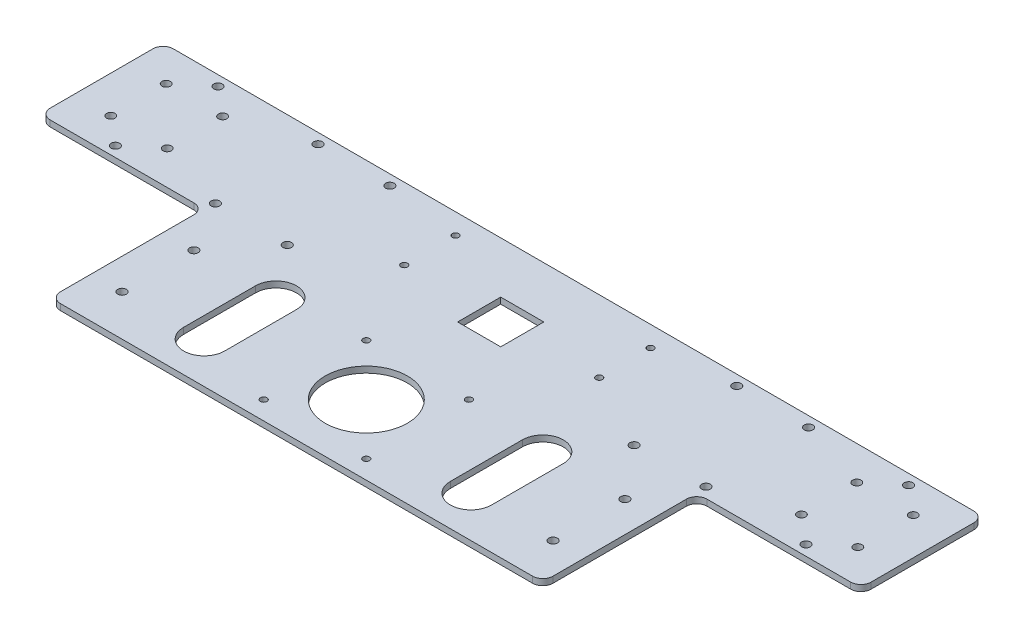
SolidWorks part; units mm, degrees
material "Thornel Mat VMA"
ref_plane "前视基准面" through (0, 0, 0) normal (0, 0, 1) x (1, 0, 0)
ref_plane "上视基准面" through (0, 0, 0) normal (0, 1, 0) x (1, 0, 0)
ref_plane "右视基准面" through (0, 0, 0) normal (1, 0, 0) x (0, 0, -1)
sketch "草图1" plane through (0, 0, 0) normal (0, 1, 0) x (1, 0, 0)
  line L0 (32.8259, -88.8718) -> (32.8259, 46.1282) construction
  line L1 (-167.1741, -13.8718) -> (232.8259, -13.8718)
  line L2 (-167.1741, -13.8718) -> (-167.1741, 46.1282)
  line L3 (-167.1741, 46.1282) -> (232.8259, 46.1282)
  line L4 (232.8259, -13.8718) -> (232.8259, 46.1282)
  line L5 (-14.6741, 36.1282) -> (80.3259, 36.1282) construction
  line L6 (-14.6741, 11.1282) -> (80.3259, 11.1282) construction
  line L7 (-87.1741, -88.8718) -> (152.8259, -88.8718)
  line L8 (-87.1741, -88.8718) -> (-87.1741, -13.8718)
  line L9 (-87.1741, -13.8718) -> (152.8259, -13.8718)
  line L10 (152.8259, -88.8718) -> (152.8259, -13.8718)
  line L11 (22.3259, 10.6282) -> (43.3259, 10.6282) construction
  line L12 (22.3259, 0.1282) -> (43.3259, 0.1282)
  line L13 (22.3259, 0.1282) -> (22.3259, 21.1282)
  line L14 (22.3259, 21.1282) -> (43.3259, 21.1282)
  line L15 (43.3259, 0.1282) -> (43.3259, 21.1282)
  line L16 (7.8259, -54.8718) -> (57.8259, -54.8718) construction
  line L17 (7.8259, -29.8718) -> (57.8259, -29.8718) construction
  line L18 (7.8259, -29.8718) -> (7.8259, -79.8718) construction
  line L19 (7.8259, -79.8718) -> (57.8259, -79.8718) construction
  line L20 (57.8259, -29.8718) -> (57.8259, -79.8718) construction
  line L21 (32.8259, 21.1282) -> (32.8259, 0.1282) construction
  line L22 (7.8259, -29.8718) -> (29.2904, -51.3362) construction
  line L23 (57.8259, -29.8718) -> (7.8259, -79.8718) construction
  line L31 (36.3615, -58.4073) -> (57.8259, -79.8718) construction
  circle A0 centre (-14.6741, 36.1282) radius 1.6
  circle A1 centre (-14.6741, 11.1282) radius 1.6
  circle A2 centre (80.3259, 11.1282) radius 1.6
  circle A3 centre (80.3259, 36.1282) radius 1.6
  circle A4 centre (7.8259, -29.8718) radius 1.6
  circle A5 centre (7.8259, -79.8718) radius 1.6
  circle A6 centre (57.8259, -79.8718) radius 1.6
  circle A7 centre (57.8259, -29.8718) radius 1.6
  circle A8 centre (32.8259, -54.8718) radius 20
  point P0 (0, 0)
  point P6 (0, -121.2547)
  point P16 (32.8259, 36.1282)
  point P19 (32.8259, 11.1282)
  point P23 (32.8259, 13.1501)
  point P30 (32.8259, -20.0664)
  point P35 (32.8259, -29.8718)
  point P44 (4.2904, -33.4073)
  point P45 (54.2904, -83.4073)
  point P46 (11.3615, -26.3362)
  point P47 (61.3615, -76.3362)
  point P48 (54.2904, -26.3362)
  point P49 (4.2904, -76.3362)
  point P50 (61.3615, -33.4073)
  point P51 (11.3615, -83.4073)
  dimension "D8" = 21
  dimension "D13" = 3.2
  dimension "D9" = 40
  dimension "D1" = 400
  dimension "D2" = 60
  dimension "D3" = 75
  dimension "D4" = 240
  dimension "D5" = 10
  dimension "D6" = 95
  dimension "D7" = 25
  dimension "D10" = 30
  dimension "D11" = 15
  dimension "D12" = 50
  dimension "D14" = 10.5
extrude "构型与裁判孔" add sketch "草图1" along normal blind 3 contours L1 L4 L3 L2 A3 L15 L12 L13 L14 A0 A1 A2 A4 A7 | L7 L10 L1 L8 A6 A5
sketch "草图2" plane through (0, 3, 0) normal (0, 1, 0) x (1, 0, 0)
  line L0 (-167.1741, 16.1282) -> (232.8259, 16.1282) construction
  line L1 (-167.1741, -13.8718) -> (-167.1741, 46.1282) construction
  line L2 (232.8259, -13.8718) -> (232.8259, 46.1282) construction
  line L3 (32.8259, 46.1282) -> (32.8259, -88.8718) construction
  line L4 (-167.1741, 46.1282) -> (232.8259, 46.1282) construction
  line L5 (-87.1741, -88.8718) -> (152.8259, -88.8718) construction
  line L6 (-149.1741, 2.6282) -> (-149.1741, 29.6282) construction
  line L7 (-121.6741, 2.6282) -> (-121.6741, 29.6282) construction
  line L8 (-149.1741, 29.6282) -> (-121.6741, 29.6282) construction
  line L9 (-51.6741, -8.8718) -> (-51.6741, 41.1282) construction
  line L10 (-135.4241, 29.6282) -> (-135.4241, 46.1282) construction
  line L11 (-135.4241, 41.1282) -> (-86.6741, 41.1282) construction
  circle A0 centre (-149.1741, 29.6282) radius 2.05
  circle A1 centre (-149.1741, 2.6282) radius 2.05
  circle A2 centre (-121.6741, 29.6282) radius 2.05
  circle A3 centre (-121.6741, 2.6282) radius 2.05
  circle A4 centre (-51.6741, 41.1282) radius 2.1
  circle A5 centre (-86.6741, 41.1282) radius 2.1
  circle A6 centre (-51.6741, -8.8718) radius 2.1
  circle A7 centre (-86.6741, -8.8718) radius 2.1
  circle A8 centre (-135.4241, 41.1282) radius 2.1
  circle A9 centre (-135.4241, -8.8718) radius 2.1
  circle A10 centre (201.0759, -8.8718) radius 2.1
  circle A11 centre (201.0759, 41.1282) radius 2.1
  circle A12 centre (152.3259, -8.8718) radius 2.1
  circle A13 centre (117.3259, -8.8718) radius 2.1
  circle A14 centre (152.3259, 41.1282) radius 2.1
  circle A15 centre (117.3259, 41.1282) radius 2.1
  circle A16 centre (187.3259, 2.6282) radius 2.05
  circle A17 centre (187.3259, 29.6282) radius 2.05
  circle A18 centre (214.8259, 2.6282) radius 2.05
  circle A19 centre (214.8259, 29.6282) radius 2.05
  point P15 (-149.1741, 16.1282)
  point P20 (-121.6741, 16.1282)
  point P25 (-51.6741, 16.1282)
  dimension "D2" = 4.1
  dimension "D4" = 5
  dimension "D5" = 4.2
  dimension "D7" = 2
  dimension "D8" = 18
  dimension "D3" = 45.5
  dimension "D1" = 27
  dimension "D6" = 70
extrude "切除-拉伸1" cut sketch "草图2" against normal through all
fillet "圆角1" radius 5 8 edges at (-87.1741, 1.5, 13.8718) (152.8259, 1.5, 13.8718) (-167.1741, 1.5, 13.8718) (-167.1741, 1.5, -46.1282) (232.8259, 1.5, -46.1282) (232.8259, 1.5, 13.8718) (152.8259, 1.5, 88.8718) (-87.1741, 1.5, 88.8718)
sketch "Sketch1" plane through (0, 0, 0) normal (0, 1, 0) x (1, 0, 0)
  line L0 (-162.1741, -13.8718) -> (-92.1741, -13.8718) construction
  line L1 (-87.1741, -83.8718) -> (-87.1741, -18.8718) construction
  line L2 (32.8259, 46.1282) -> (32.8259, -164.9495) construction
  line L3 (-162.1741, 46.1282) -> (227.8259, 46.1282) construction
  line L4 (-72.1741, -33.8718) -> (-72.1741, -68.8718) construction
  line L5 (-32.1741, -33.8718) -> (-32.1741, -68.8718) construction
  line L6 (-32.1741, -68.8718) -> (-32.1741, -33.8718) construction
  line L7 (-42.1741, -68.8718) -> (-42.1741, -33.8718)
  line L8 (-22.1741, -68.8718) -> (-22.1741, -33.8718)
  line L9 (97.8259, -68.8718) -> (97.8259, -33.8718) construction
  line L10 (107.8259, -68.8718) -> (107.8259, -33.8718)
  line L11 (87.8259, -68.8718) -> (87.8259, -33.8718)
  circle A0 centre (-72.1741, -33.8718) radius 2.1
  circle A1 centre (-72.1741, -68.8718) radius 2.1
  circle A2 centre (137.8259, -68.8718) radius 2.1
  circle A3 centre (137.8259, -33.8718) radius 2.1
  arc A4 (-42.1741, -68.8718) -> (-22.1741, -68.8718) centre (-32.1741, -68.8718) ccw
  arc A5 (-22.1741, -33.8718) -> (-42.1741, -33.8718) centre (-32.1741, -33.8718) ccw
  arc A6 (107.8259, -68.8718) -> (87.8259, -68.8718) centre (97.8259, -68.8718) cw
  arc A7 (87.8259, -33.8718) -> (107.8259, -33.8718) centre (97.8259, -33.8718) cw
  point P18 (-32.1741, -51.3718)
  point P20 (-32.1741, -51.3718)
  point P27 (97.8259, -51.3718)
  dimension "D1" = 4.2
  dimension "D2" = 20
  dimension "D3" = 35
  dimension "D4" = 15
  dimension "D5" = 15
  dimension "D7" = 10
  dimension "D6" = 40
extrude "Cut-Extrude4" cut sketch "Sketch1" along normal through all
